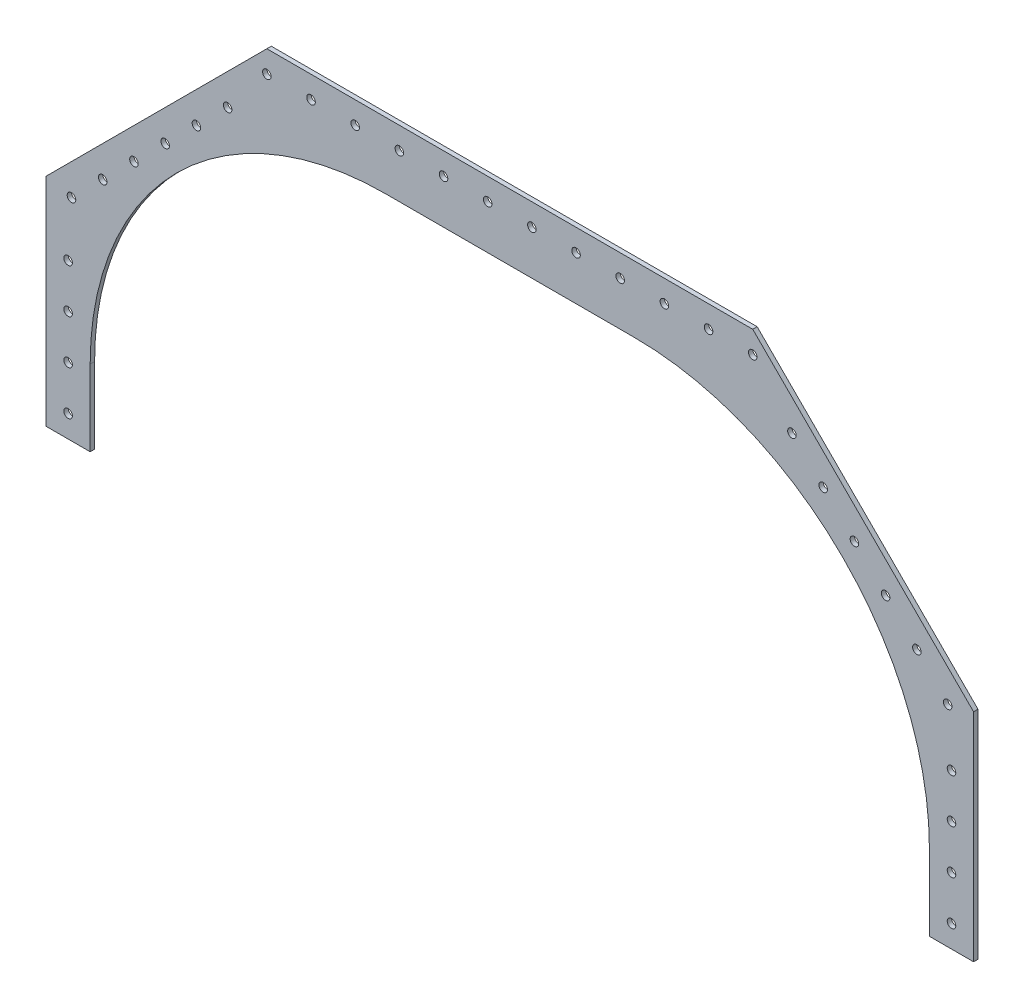
SolidWorks part; units mm, degrees
ref_plane "Front" through (0, 0, 0) normal (0, 0, 1) x (1, 0, 0)
ref_plane "Top" through (0, 0, 0) normal (0, 1, 0) x (1, 0, 0)
ref_plane "Right" through (0, 0, 0) normal (1, 0, 0) x (0, 0, -1)
sketch "Sketch1" plane through (0, 0, 0) normal (0, 0, 1) x (1, 0, 0)
  line L1 (266.7, 0) -> (241.3, 0)
  line L2 (266.7, 0) -> (266.7, 124.5235)
  line L3 (139.7, 251.5235) -> (-139.7, 251.5235)
  line L4 (-266.7, 0) -> (-266.7, 124.5235)
  line L5 (143.5293, 251.5235) -> (-143.5293, 251.5235) construction
  line L8 (-139.7, 251.5235) -> (-266.7, 124.5235)
  line L9 (266.7, 124.5235) -> (139.7, 251.5235)
  line L10 (241.3, 0) -> (241.3, 43.7012)
  line L12 (71.5777, 213.4235) -> (-71.5777, 213.4235)
  line L14 (-241.3, 43.7012) -> (-241.3, 0)
  line L16 (-241.3, 0) -> (-241.3, 114.0025) construction
  line L17 (241.3, 0) -> (241.3, 114.0025) construction
  line L18 (266.7, 0) -> (266.7, 88.6025) construction
  line L19 (266.7, 88.6025) -> (129.179, 226.1235) construction
  line L22 (-241.3, 0) -> (-266.7, 0)
  line L24 (-266.7, 88.6025) -> (-129.179, 226.1235) construction
  line L25 (165.1, 226.1235) -> (-165.1, 226.1235) construction
  arc A0 (241.3, 43.7012) -> (71.5777, 213.4235) centre (71.5777, 43.7012) ccw
  arc A1 (-71.5777, 213.4235) -> (-241.3, 43.7012) centre (-71.5777, 43.7012) ccw
  point P0 (0, 0)
  point P1 (-266.7, 251.5235)
  point P3 (266.7, 251.5235)
  point P24 (-241.3, 43.7012)
  dimension "D1" = 12.7
extrude "Boss-Extrude1" add sketch "Sketch1" along normal blind 2.54
hole_wizard "#8 Clearance Hole1" positions "Sketch2" profile "Sketch3" hole size "#8" standard "ANSI Inch" end condition through all
sketch "Sketch2" plane through (0, 0, 0) normal (0, 0, -1) x (-1, 0, 0)
  point P0 (-254, 12.7635)
  point P2 (-254, 38.1635)
  point P4 (-254, 63.5635)
  point P6 (-254, 88.9635)
  point P19 (-251.8048, 120.7779)
  point P21 (-234.0837, 139.1793)
  point P24 (-216.1232, 157.1398)
  point P27 (-198.1626, 175.1003)
  point P30 (-180.2021, 193.0609)
  point P33 (-162.2416, 211.0214)
  point P36 (-114.3, 238.8235)
  point P39 (-88.9, 238.8235)
  point P42 (-63.5, 238.8235)
  point P45 (-38.1, 238.8235)
  point P48 (-12.7, 238.8235)
  point P51 (12.7, 238.8235)
  point P54 (38.1, 238.8235)
  point P57 (63.5, 238.8235)
  point P60 (88.9, 238.8235)
  point P63 (114.3, 238.8235)
  point P66 (139.7, 238.8235)
  point P69 (162.2416, 211.0214)
  point P72 (180.2021, 193.0609)
  point P75 (198.1626, 175.1003)
  point P78 (216.1232, 157.1398)
  point P81 (234.0837, 139.1793)
  point P84 (252.0442, 121.2188)
  point P87 (254, 88.9635)
  point P90 (254, 63.5635)
  point P93 (254, 38.1635)
  point P96 (254, 12.7635)
  point P99 (-139.7, 238.8235)
sketch "Sketch3" plane through (254, 12.7635, 0) normal (1, 0, 0) x (0, 1, 0)
  line L0 (0, 0) -> (0, 2.54)
  line L1 (0, 2.54) -> (2.4574, 2.54)
  line L2 (2.4574, 2.54) -> (2.4574, 0)
  line L5 (2.4574, 0) -> (0, 0)
  line L11 (0, -6.35) -> (0, 107.95) construction
  dimension "Thru Hole Dia." = 4.9149
  dimension "Thru Hole Depth" = 2.54
